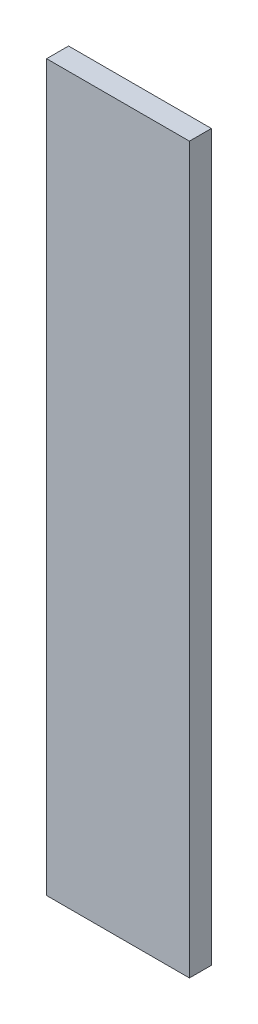
SolidWorks part; units mm, degrees
ref_plane "Plan de face" through (0, 0, 0) normal (0, 0, 1) x (1, 0, 0)
ref_plane "Plan de dessus" through (0, 0, 0) normal (0, 1, 0) x (1, 0, 0)
ref_plane "Plan de droite" through (0, 0, 0) normal (1, 0, 0) x (0, 0, -1)
sketch "Esquisse1" plane through (0, 0, 0) normal (0, 0, 1) x (1, 0, 0)
  line L1 (5.85, 29.685) -> (-5.85, 29.685)
  line L2 (5.85, 29.685) -> (5.85, -29.685)
  line L3 (5.85, -29.685) -> (-5.85, -29.685)
  line L4 (-5.85, 29.685) -> (-5.85, -29.685)
  line L5 (5.85, 29.685) -> (-5.85, -29.685) construction
  line L6 (5.85, -29.685) -> (-5.85, 29.685) construction
  point P0 (0, 0)
extrude "Boss.-Extru.1" add sketch "Esquisse1" along normal blind 1.8
